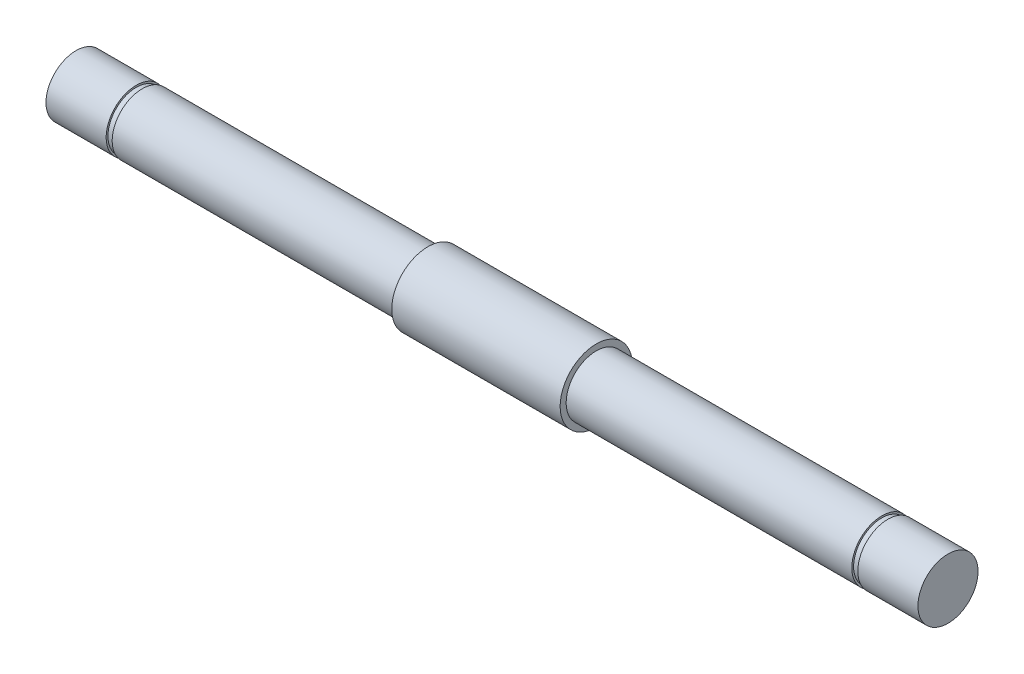
SolidWorks part; units mm, degrees
ref_plane "Plan de face" through (0, 0, 0) normal (0, 0, 1) x (1, 0, 0)
ref_plane "Plan de dessus" through (0, 0, 0) normal (0, 1, 0) x (1, 0, 0)
ref_plane "Plan de droite" through (0, 0, 0) normal (1, 0, 0) x (0, 0, -1)
sketch "Esquisse1" plane through (0, 0, 0) normal (0, 0, 1) x (1, 0, 0)
  line L0 (0, 0) -> (71.9275, 0) construction
  line L9 (14, 6) -> (-14, 6)
  line L18 (-72.5, 5) -> (-72.5, 0)
  line L19 (-72.5, 0) -> (72.5, 0)
  line L20 (72.5, 0) -> (72.5, 5)
  line L23 (-14, 6) -> (-14, 5)
  line L24 (72.5, 5) -> (62.5, 5)
  line L25 (62.5, 5) -> (62.5, 4.7)
  line L26 (62.5, 4.7) -> (61.5, 4.7)
  line L27 (61.5, 4.7) -> (61.5, 5)
  line L28 (61.5, 5) -> (14, 5)
  line L29 (14, 6) -> (14, 5)
  line L30 (-72.5, 5) -> (-62.5, 5)
  line L31 (-62.5, 5) -> (-62.5, 4.7)
  line L32 (-62.5, 4.7) -> (-61.5, 4.7)
  line L33 (-61.5, 4.7) -> (-61.5, 5)
  line L34 (-61.5, 5) -> (-14, 5)
  dimension "D2" = 5
  dimension "D3" = 10
  dimension "D4" = 6
  dimension "D5" = 47.5
  dimension "D6" = 1
  dimension "D7" = 5
  dimension "D8" = 0.3
  dimension "D9" = 1
  dimension "D10" = 0.3
  dimension "D11" = 10
  dimension "D12" = 1
  dimension "D13" = 5
  dimension "D14" = 28
  dimension "D15" = 47.5
revolve "Révolution1" add sketch "Esquisse1" angle 360 about L0
